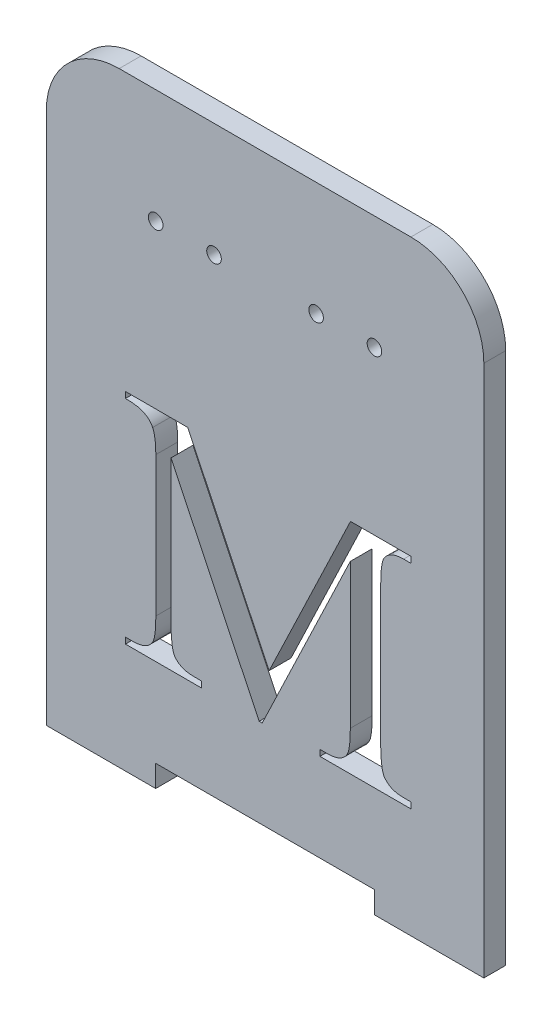
SolidWorks part; units mm, degrees
ref_plane "Front Plane" through (0, 0, 0) normal (0, 0, 1) x (1, 0, 0)
ref_plane "Top Plane" through (0, 0, 0) normal (0, 1, 0) x (1, 0, 0)
ref_plane "Right Plane" through (0, 0, 0) normal (1, 0, 0) x (0, 0, -1)
sketch "Sketch1" plane through (0, 0, 0) normal (0, 0, 1) x (1, 0, 0)
  line L1 (15, 0) -> (45, 0)
  line L2 (0, 0) -> (0, 70)
  line L3 (10, 80) -> (50, 80)
  line L4 (60, 0) -> (60, 70)
  line L6 (0, 0) -> (0, -3)
  line L7 (0, -3) -> (15, -3)
  line L8 (15, 0) -> (15, -3)
  line L10 (60, 0) -> (60, -3)
  line L11 (60, -3) -> (45, -3)
  line L12 (45, 0) -> (45, -3)
  arc A0 (50, 80) -> (60, 70) centre (50, 70) cw
  arc A1 (0, 70) -> (10, 80) centre (10, 70) cw
  point P7 (60, 80)
  point P10 (0, 80)
  dimension "D3" = 10
  dimension "D1" = 60
  dimension "D2" = 80
  dimension "D4" = 15
  dimension "D5" = 3
  dimension "D6" = 15
  dimension "D7" = 3
extrude "Boss-Extrude1" add sketch "Sketch1" along normal blind 3
sketch "Sketch2" plane through (0, 0, 3) normal (0, 0, 1) x (1, 0, 0)
  text T0 "M" font "Times New Roman" height 30
extrude "Cut-Extrude1" cut sketch "Sketch2" against normal blind 3
sketch "Sketch3" plane through (0, 0, 3) normal (0, 0, 1) x (1, 0, 0)
  line L0 (45, 64.3775) -> (60, 64.3775) construction
  line L1 (60, -3) -> (60, 70) construction
  line L2 (15, 64.3775) -> (0, 64.3775) construction
  line L3 (0, 70) -> (0, -3) construction
  line L4 (37, 64.3775) -> (45, 64.3775) construction
  line L5 (23, 64.3775) -> (15, 64.3775) construction
  circle A0 centre (15, 64.3775) radius 1
  circle A1 centre (45, 64.3775) radius 1
  circle A2 centre (23, 64.3775) radius 1
  circle A3 centre (37, 64.3775) radius 1
  dimension "D1" = 2
  dimension "D2" = 30
  dimension "D3" = 8
extrude "Cut-Extrude2" cut sketch "Sketch3" against normal blind 3
